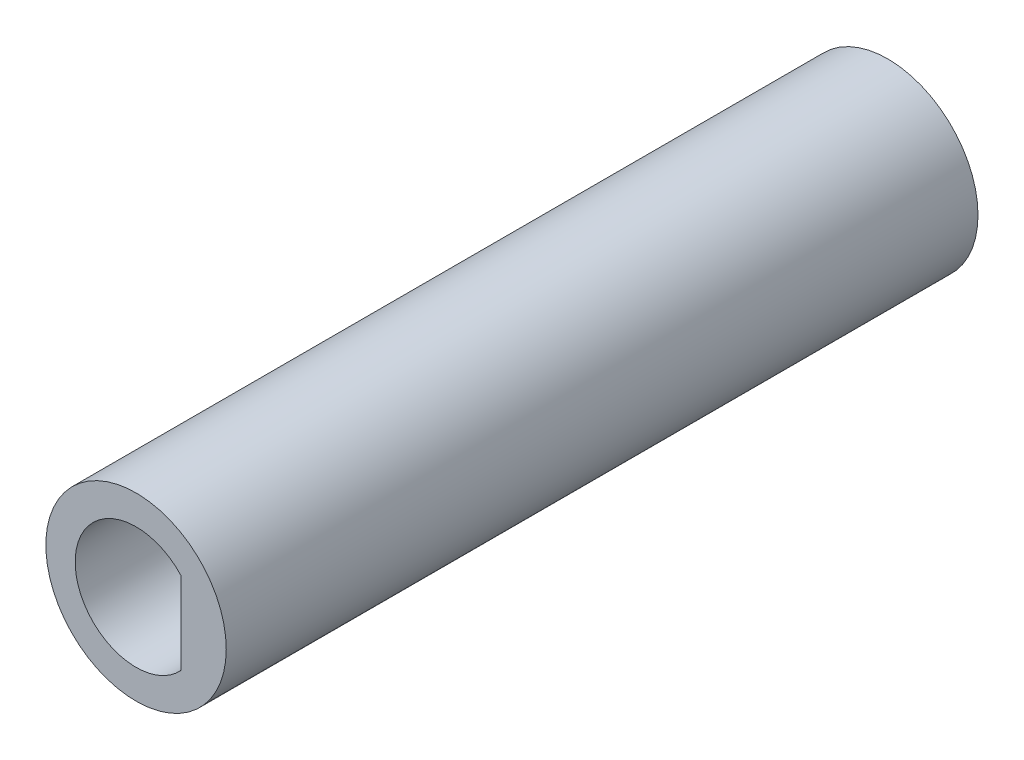
SolidWorks part; units mm, degrees
ref_plane "Front Plane" through (0, 0, 0) normal (0, 0, 1) x (1, 0, 0)
ref_plane "Top Plane" through (0, 0, 0) normal (0, 1, 0) x (1, 0, 0)
ref_plane "Right Plane" through (0, 0, 0) normal (1, 0, 0) x (0, 0, -1)
sketch "Sketch1" plane through (0, 0, 0) normal (0, 0, 1) x (1, 0, 0)
  line L0 (3, 2.7208) -> (3, -2.7208)
  circle A1 centre (0, 0) radius 6
  arc A2 (3, 2.7208) -> (3, -2.7208) centre (0, 0) ccw
  dimension "D1" = 12
  dimension "D2" = 4.05
  dimension "D3" = 3
extrude "Boss-Extrude1" add sketch "Sketch1" along normal blind 15
sketch "Sketch2" plane through (0, 0, 0) normal (0, 0, 1) x (1, 0, 0)
  circle A0 centre (0, 0) radius 6
  circle A1 centre (0, 0) radius 6 construction
extrude "Boss-Extrude2" add sketch "Sketch2" against normal blind 35
